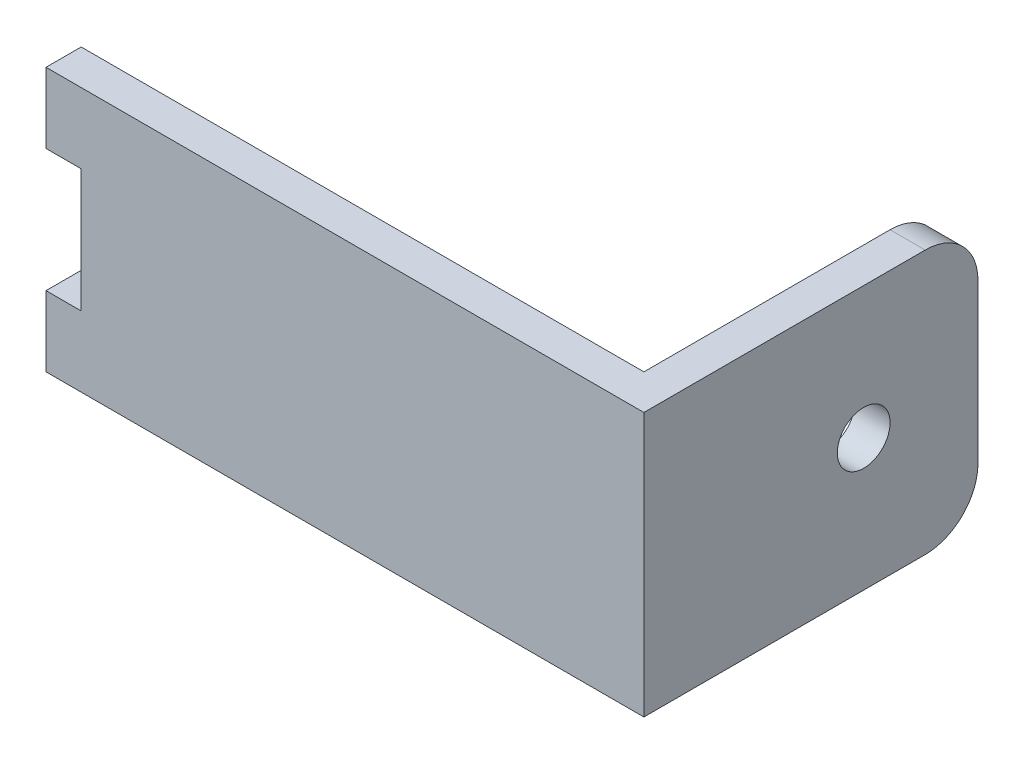
SolidWorks part; units mm, degrees
material "ABS"
ref_plane "Front Plane" through (0, 0, 0) normal (0, 0, 1) x (1, 0, 0)
ref_plane "Top Plane" through (0, 0, 0) normal (0, 1, 0) x (1, 0, 0)
ref_plane "Right Plane" through (0, 0, 0) normal (1, 0, 0) x (0, 0, -1)
sketch "Sketch1" plane through (0, 0, 0) normal (0, 0, 1) x (1, 0, 0)
  line L1 (0, 0) -> (30, 0)
  line L2 (0, 0) -> (0, 15)
  line L3 (0, 15) -> (30, 15)
  line L4 (30, 0) -> (30, 15)
  dimension "D1" = 15
  dimension "D2" = 30
extrude "Boss-Extrude1" add sketch "Sketch1" along normal blind 2
sketch "Sketch2" plane through (30, 0, 0) normal (1, 0, 0) x (0, 0, -1)
  line L1 (-2, 0) -> (17, 0)
  line L2 (-2, 0) -> (-2, 15)
  line L3 (-2, 15) -> (17, 15)
  line L4 (17, 0) -> (17, 15)
  dimension "D1" = 15
  dimension "D2" = 19
extrude "Boss-Extrude2" add sketch "Sketch2" along normal blind 2
sketch "Sketch3" plane through (32, 0, 0) normal (1, 0, 0) x (0, 0, -1)
  line L0 (-4.6221, 7.5) -> (21.3694, 7.5) construction
  line L1 (10.5, 17.9651) -> (10.5, -3.4854) construction
  line L2 (-2, 15) -> (-2, 0) construction
  line L3 (-2, 0) -> (17, 0) construction
  circle A0 centre (10.5, 7.5) radius 1.5
  point P6 (10.5, 7.5)
  dimension "D3" = 3
  dimension "D1" = 12.5
  dimension "D2" = 7.5
extrude "Cut-Extrude1" cut sketch "Sketch3" against normal blind 2
fillet "Fillet1" radius 3 2 edges at (31, 0, -17) (31, 15, -17)
sketch "Sketch4" plane through (0, 0, 0) normal (-1, 0, 0) x (0, 0, 1)
  line L0 (2, 15) -> (2, 0) construction
  line L1 (0, 15) -> (2, 15)
  line L2 (0, 15) -> (0, 11)
  line L3 (0, 11) -> (2, 11)
  line L4 (2, 15) -> (2, 11)
  line L5 (0, 0) -> (0, 15) construction
  line L6 (2, 0) -> (0, 0)
  line L7 (2, 0) -> (2, 4)
  line L8 (2, 4) -> (0, 4)
  line L9 (0, 0) -> (0, 4)
  dimension "D1" = 4
  dimension "D2" = 4
extrude "Boss-Extrude3" add sketch "Sketch4" along normal blind 2
